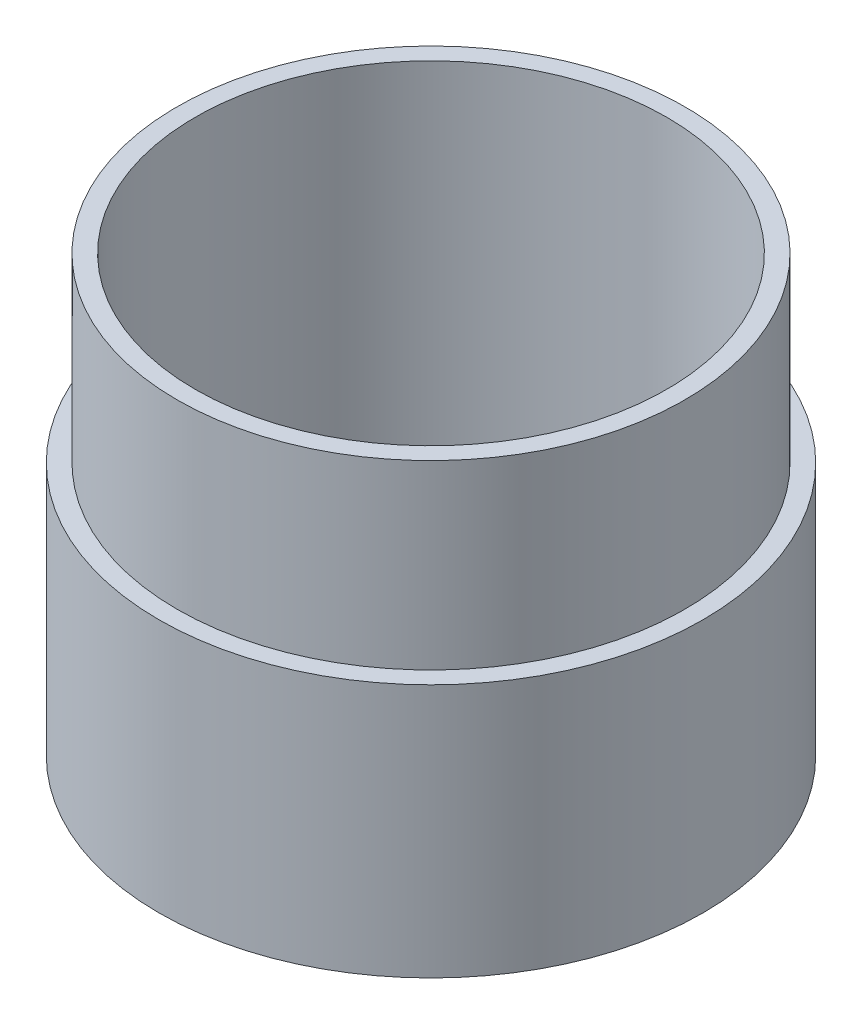
SolidWorks part; units mm, degrees
ref_plane "Front Plane" through (0, 0, 0) normal (0, 0, 1) x (1, 0, 0)
ref_plane "Top Plane" through (0, 0, 0) normal (0, 1, 0) x (1, 0, 0)
ref_plane "Right Plane" through (0, 0, 0) normal (1, 0, 0) x (0, 0, -1)
sketch "Sketch1" plane through (0, 0, 0) normal (0, 1, 0) x (1, 0, 0)
  circle A0 centre (0, 0) radius 37.5
  dimension "D1" = 75
extrude "Boss-Extrude1" add sketch "Sketch1" along normal blind 35
sketch "Sketch2" plane through (0, 35, 0) normal (0, 1, 0) x (1, 0, 0)
  circle A0 centre (0, 0) radius 35
  dimension "D1" = 70
extrude "Boss-Extrude2" add sketch "Sketch2" along normal blind 25
sketch "Sketch3" plane through (0, 60, 0) normal (0, 1, 0) x (1, 0, 0)
  circle A0 centre (0, 0) radius 32.5
  dimension "D1" = 65
extrude "Cut-Extrude1" cut sketch "Sketch3" against normal blind 59
